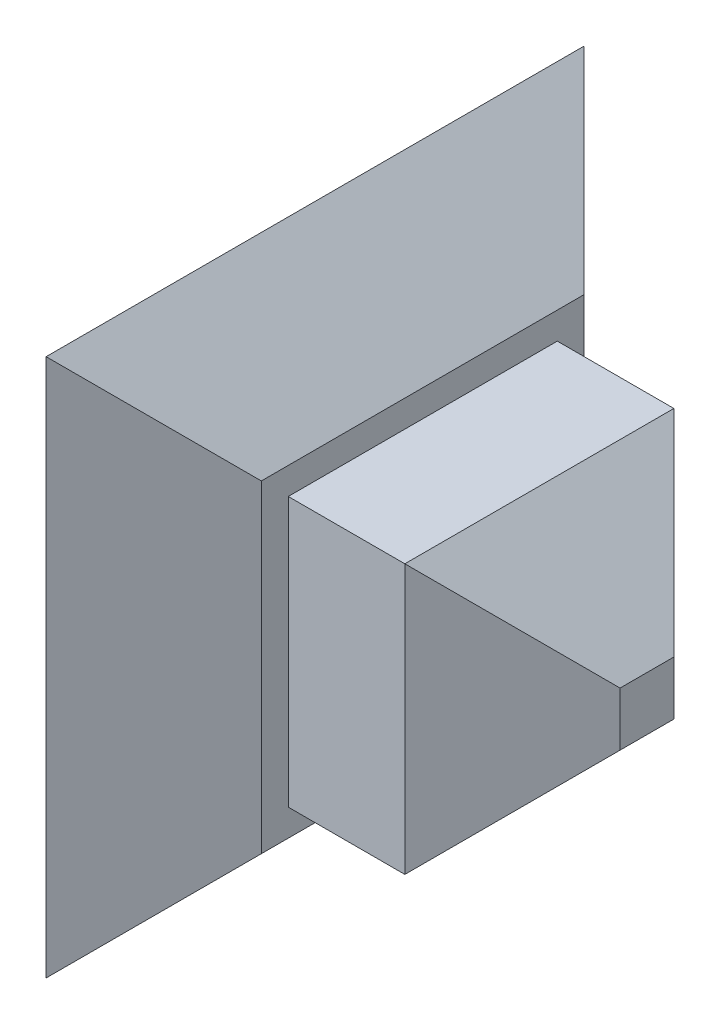
SolidWorks part; units mm, degrees
ref_plane "Front Plane" through (0, 0, 0) normal (0, 0, 1) x (1, 0, 0)
ref_plane "Top Plane" through (0, 0, 0) normal (0, 1, 0) x (1, 0, 0)
ref_plane "Right Plane" through (0, 0, 0) normal (1, 0, 0) x (0, 0, -1)
sketch "Sketch4" plane through (0, 0, 0) normal (1, 0, 0) x (0, 0, -1)
  line L1 (19.05, 19.05) -> (-19.05, 19.05)
  line L2 (19.05, 19.05) -> (19.05, -19.05)
  line L3 (19.05, -19.05) -> (-19.05, -19.05)
  line L4 (-19.05, 19.05) -> (-19.05, -19.05)
  line L5 (19.05, 19.05) -> (-19.05, -19.05) construction
  line L6 (19.05, -19.05) -> (-19.05, 19.05) construction
  point P0 (0, 0)
  dimension "D1" = 38.1
extrude "Boss-Extrude2" add sketch "Sketch4" along normal blind 15.24 draft 45 and the other way blind 19.05
ref_plane "Plane1" through (40.64, 0, 0) normal (-1, 0, 0) x (0, 0, 1)
sketch "Sketch10" plane through (-19.05, 0, 0) normal (-1, 0, 0) x (0, 0, 1)
  line L1 (-25.4, 25.4) -> (25.4, 25.4)
  line L2 (-25.4, 25.4) -> (-25.4, -25.4)
  line L3 (-25.4, -25.4) -> (25.4, -25.4)
  line L4 (25.4, 25.4) -> (25.4, -25.4)
  line L5 (-25.4, 25.4) -> (25.4, -25.4) construction
  line L6 (-25.4, -25.4) -> (25.4, 25.4) construction
  point P0 (0, 0)
  dimension "D1" = 50.8
extrude "Boss-Extrude3" add sketch "Sketch10" along normal blind 12.7 draft 45 and the other way blind 2.54 draft 45 draft outward yes
